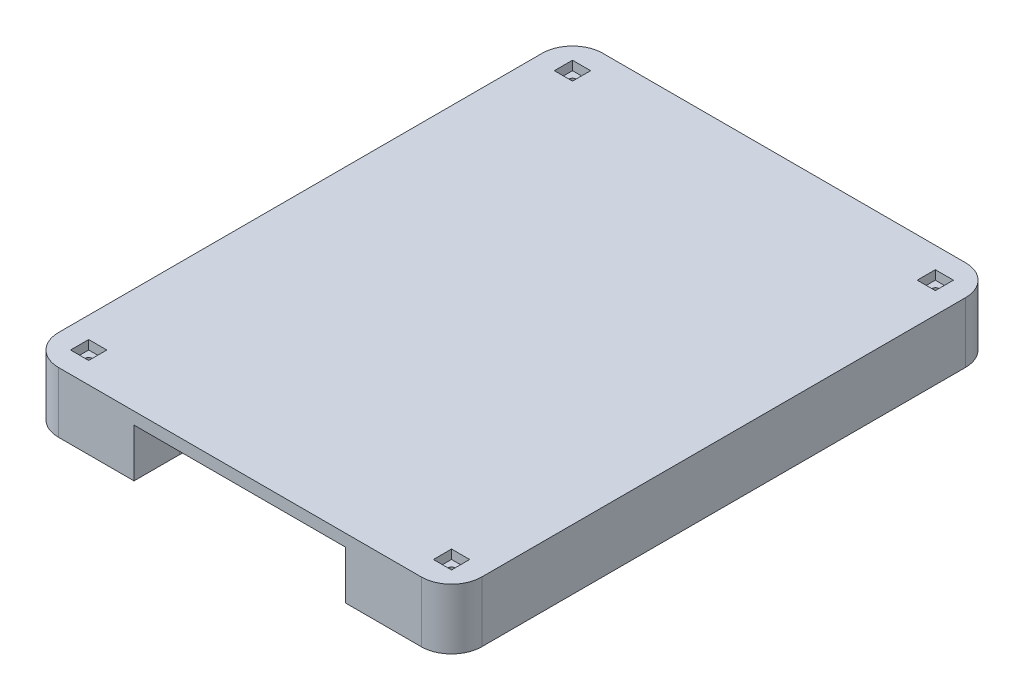
SolidWorks part; units mm, degrees
ref_plane "前视基准面" through (0, 0, 0) normal (0, 0, 1) x (1, 0, 0)
ref_plane "上视基准面" through (0, 0, 0) normal (0, 1, 0) x (1, 0, 0)
ref_plane "右视基准面" through (0, 0, 0) normal (1, 0, 0) x (0, 0, -1)
sketch "草图1" plane through (0, 0, 0) normal (0, 1, 0) x (1, 0, 0)
  line L1 (100, -100) -> (-100, -100)
  line L2 (100, -100) -> (100, 100)
  line L3 (100, 100) -> (-100, 100)
  line L4 (-100, -100) -> (-100, 100)
  line L5 (100, -100) -> (-100, 100) construction
  line L6 (100, 100) -> (-100, -100) construction
  point P1 (0, 0)
  dimension "D1" = 200
  dimension "D2" = 200
extrude "凸台-拉伸1" add sketch "草图1" along normal blind 20
sketch "草图2" plane through (0, 20, 0) normal (0, 1, 0) x (1, 0, 0)
  line L1 (70, -90) -> (-70, -90)
  line L2 (70, -90) -> (70, 90)
  line L3 (70, 90) -> (-70, 90)
  line L4 (-70, -90) -> (-70, 90)
  line L5 (70, -90) -> (-70, 90) construction
  line L6 (70, 90) -> (-70, -90) construction
  line L7 (100, -100) -> (-100, -100)
  line L8 (100, -100) -> (100, 100)
  line L9 (100, 100) -> (-100, 100)
  line L10 (-100, -100) -> (-100, 100)
  line L11 (100, -100) -> (-100, 100) construction
  line L12 (100, 100) -> (-100, -100) construction
  point P0 (0, 0)
  point P6 (0, 0)
  dimension "D1" = 140
  dimension "D2" = 180
extrude "切除-拉伸2" cut sketch "草图2" against normal through all
fillet "圆角1" radius 10 1 edges at (-70, 10, -90)
fillet "圆角2" radius 10 1 edges at (70, 10, -90)
fillet "圆角3" radius 10 1 edges at (70, 10, 90)
fillet "圆角4" radius 10 1 edges at (-70, 10, 90)
sketch "草图4" plane through (0, 0, 0) normal (0, -1, 0) x (1, 0, 0)
  line L5 (-60, 90) -> (60, 90) construction
  line L82 (-70, -80) -> (-70, 80) construction
  line L83 (-59.5, 84.9749) -> (-59.5, 86)
  line L95 (-59.5, 74) -> (-60.5, 74)
  line L97 (-59.5, 74) -> (-59.5, 75.0251)
  line L102 (-59.5, 86) -> (-60.5, 86)
  line L103 (-60.5, 74) -> (-60.5, 75.0251)
  line L108 (-66, 79.5) -> (-64.9749, 79.5)
  line L109 (-66, 79.5) -> (-66, 80.5)
  line L110 (-66, 80.5) -> (-64.9749, 80.5)
  line L111 (-54, 79.5) -> (-54, 80.5)
  line L115 (-60.5, 84.9749) -> (-60.5, 86)
  line L116 (-55.0251, 80.5) -> (-54, 80.5)
  line L120 (-55.0251, 79.5) -> (-54, 79.5)
  arc A5 (-60.5, 84.9749) -> (-64.9749, 80.5) centre (-60, 80) ccw
  arc A6 (-55.0251, 80.5) -> (-59.5, 84.9749) centre (-60, 80) ccw
  arc A7 (-59.5, 75.0251) -> (-55.0251, 79.5) centre (-60, 80) ccw
  arc A8 (-64.9749, 79.5) -> (-60.5, 75.0251) centre (-60, 80) ccw
  point P0 (0, 0)
  point P2 (-60, 80)
  dimension "D3" = 1
  dimension "D4" = 12
  dimension "D1" = 10
  dimension "D2" = 10
  dimension "D5" = 1
  dimension "D6" = 12
extrude "切除-拉伸4" cut sketch "草图4" against normal blind 5
mirror "镜向3" about plane through (0, 0, 0) normal (1, 0, 0) of "切除-拉伸4" second plane through (0, 0, 0) second plane normal (0, 0, 1)
sketch "草图5" plane through (0, 0, 0) normal (0, -1, 0) x (1, 0, 0)
  line L1 (60, -80) -> (-60, -80) construction
  line L2 (60, -80) -> (60, 80) construction
  line L3 (60, 80) -> (-60, 80) construction
  line L4 (-60, -80) -> (-60, 80) construction
  line L5 (60, -80) -> (-60, 80) construction
  line L6 (60, 80) -> (-60, -80) construction
  circle A0 centre (-60, 80) radius 5
  point P0 (0, 0)
  dimension "D3" = 10
  dimension "D1" = 120
  dimension "D2" = 160
extrude "切除-拉伸5" cut sketch "草图5" against normal blind 6.2
sketch "草图7" plane through (0, 0, 0) normal (0, -1, 0) x (1, 0, 0)
  line L0 (-60, 90) -> (60, 90) construction
  line L1 (35, 110) -> (-35, 110)
  line L2 (35, 110) -> (35, 75)
  line L3 (30, 70) -> (-30, 70)
  line L4 (-35, 110) -> (-35, 75)
  line L5 (35, 110) -> (-35, 70) construction
  line L6 (35, 70) -> (-35, 110) construction
  arc A0 (-30, 70) -> (-35, 75) centre (-30, 75) cw
  arc A1 (30, 70) -> (35, 75) centre (30, 75) ccw
  point P0 (0, 90)
  dimension "D3" = 5
  dimension "D4" = 5
  dimension "D1" = 70
  dimension "D2" = 40
extrude "切除-拉伸7" cut sketch "草图7" against normal blind 16
mirror "镜向6" about plane through (0, 0, 0) normal (0, 0, 1) of "切除-拉伸7"
sketch "草图8" plane through (0, 0, 0) normal (0, -1, 0) x (1, 0, 0)
  line L5 (40.5, -40.5) -> (-40.5, -40.5) construction
  line L6 (40.5, -40.5) -> (40.5, 40.5) construction
  line L7 (40.5, 40.5) -> (-40.5, 40.5) construction
  line L8 (-40.5, -40.5) -> (-40.5, 40.5) construction
  line L9 (40.5, -40.5) -> (-40.5, 40.5) construction
  line L10 (40.5, 40.5) -> (-40.5, -40.5) construction
  circle A4 centre (-40.5, 40.5) radius 4.1
  point P0 (0, 0)
  dimension "D1" = 81
  dimension "D2" = 81
extrude "切除-拉伸8" cut sketch "草图8" against normal blind 4
draft "拔模2" type of draft neutral plane draft angle 10 faces to draft 1 face at (-40.5, 4, 36.4) neutral plane through (-40.5, 4, 40.5) neutral plane normal (0, -1, 0) parameters "D1"=10
mirror "镜向10" about plane through (0, 0, 0) normal (1, 0, 0) of "拔模2", "切除-拉伸8"
mirror "镜向11" about plane through (0, 0, 0) normal (0, 0, 1) of "切除-拉伸8", "拔模2"
sketch "草图14" plane through (0, 20, 0) normal (0, 1, 0) x (1, 0, 0)
  line L1 (60, -80) -> (-60, -80) construction
  line L2 (60, -80) -> (60, 80) construction
  line L3 (60, 80) -> (-60, 80) construction
  line L4 (-60, -80) -> (-60, 80) construction
  line L5 (60, -80) -> (-60, 80) construction
  line L6 (60, 80) -> (-60, -80) construction
  line L7 (-57, 77) -> (-63, 77)
  line L8 (-57, 77) -> (-57, 83)
  line L9 (-57, 83) -> (-63, 83)
  line L10 (-63, 77) -> (-63, 83)
  line L11 (-57, 77) -> (-63, 83) construction
  line L12 (-57, 83) -> (-63, 77) construction
  point P0 (0, 0)
  dimension "D1" = 120
  dimension "D2" = 160
  dimension "D3" = 6
  dimension "D4" = 6
extrude "切除-拉伸9" cut sketch "草图14" against normal blind 3
mirror "镜向12" about plane through (0, 0, 0) normal (1, 0, 0) of "切除-拉伸9" second plane through (0, 0, 0) second plane normal (0, 0, 1)
sketch "草图18" plane through (0, 0, 0) normal (0, -1, 0) x (1, 0, 0)
  line L0 (-60, 90) -> (-35, 90) construction
  line L1 (-70, -80) -> (-70, 80) construction
  circle A0 centre (-60, 80) radius 1.2
  dimension "D1" = 10
  dimension "D2" = 10
extrude "切除-拉伸11" cut sketch "草图18" against normal through all
mirror "镜向16" about plane through (0, 0, 0) normal (1, 0, 0) of "切除-拉伸11" second plane through (0, 0, 0) second plane normal (0, 0, 1)
